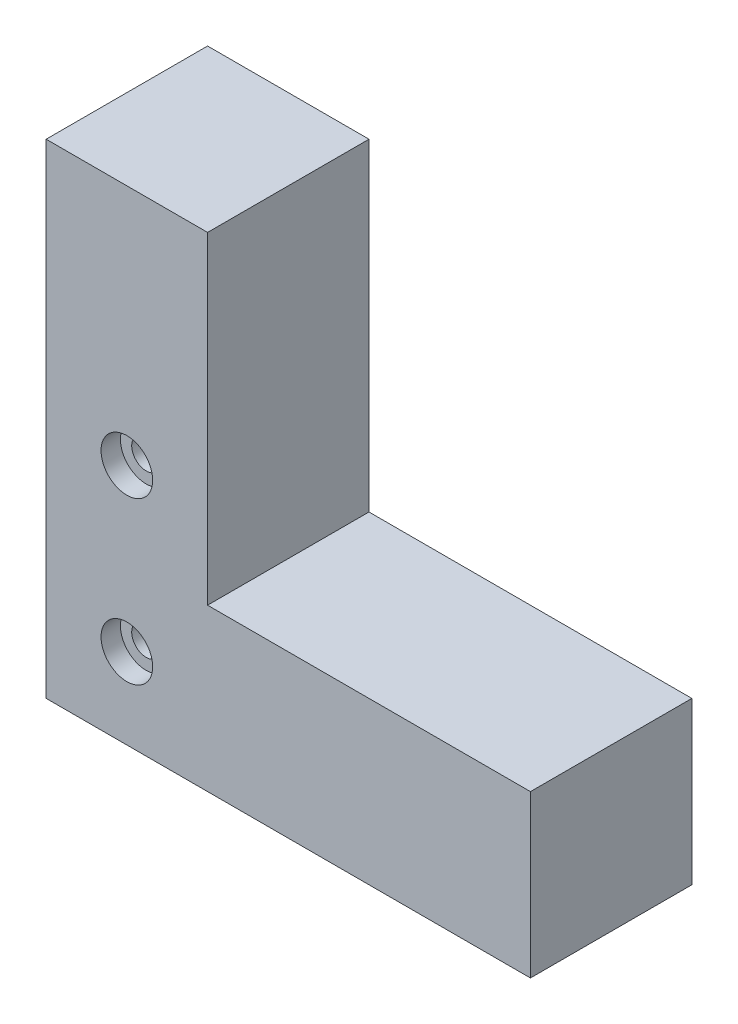
SolidWorks part; units mm, degrees
ref_plane "Front Plane" through (0, 0, 0) normal (0, 0, 1) x (1, 0, 0)
ref_plane "Top Plane" through (0, 0, 0) normal (0, 1, 0) x (1, 0, 0)
ref_plane "Right Plane" through (0, 0, 0) normal (1, 0, 0) x (0, 0, -1)
sketch "Sketch1" plane through (0, 0, 0) normal (0, 0, 1) x (1, 0, 0)
  line L0 (-25, -25) -> (50, -25)
  line L2 (0, 0) -> (0, 50)
  line L3 (0, 50) -> (-25, 50)
  line L4 (-25, -25) -> (-25, 50)
  line L5 (0, 0) -> (50, 0)
  line L8 (50, 0) -> (50, -25)
  dimension "D1" = 50
  dimension "D2" = 25
  dimension "D3" = 50
  dimension "D4" = 25
extrude "Boss-Extrude1" add sketch "Sketch1" along normal blind 25
sketch "Sketch2" plane through (0, 0, 25) normal (0, 0, 1) x (1, 0, 0)
  line L0 (-25, -25) -> (50, -25) construction
  line L1 (-25, 50) -> (-25, -25) construction
  circle A0 centre (-12.5, -12.5) radius 2.25
  circle A1 centre (-12.5, 12.5) radius 2.25
  dimension "D2" = 4.5
  dimension "D3" = 4.5
  dimension "D1" = 25
  dimension "D4" = 12.5
  dimension "D5" = 12.5
  dimension "D6" = 12.5
extrude "Cut-Extrude1" cut sketch "Sketch2" against normal blind 25
sketch "Sketch3" plane through (0, 0, 25) normal (0, 0, 1) x (1, 0, 0)
  circle A0 centre (-12.5, 12.5) radius 4
  circle A1 centre (-12.5, -12.5) radius 4
  dimension "D1" = 8
  dimension "D2" = 8
extrude "Cut-Extrude2" cut sketch "Sketch3" against normal blind 3
